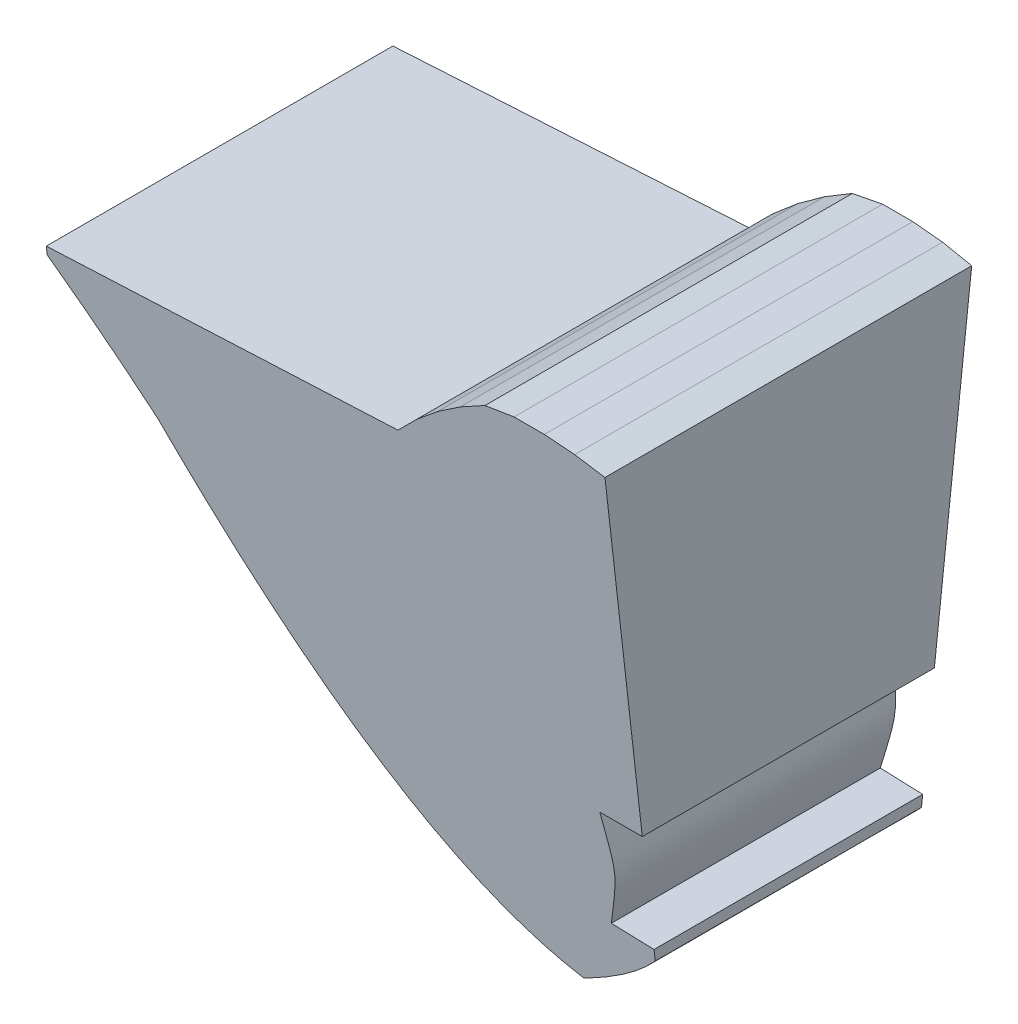
SolidWorks part; units mm, degrees
ref_plane "Alzado" through (0, 0, 0) normal (0, 0, 1) x (1, 0, 0)
ref_plane "Planta" through (0, 0, 0) normal (0, 1, 0) x (1, 0, 0)
ref_plane "Vista lateral" through (0, 0, 0) normal (1, 0, 0) x (0, 0, -1)
sketch "Croquis1" plane through (0, 0, 0) normal (0, 0, 1) x (1, 0, 0)
  line L0 (-8.9818, 12.6082) -> (-23.0359, 11.8716) construction
  line L1 (-8.9818, 12.6082) -> (-23.0359, 11.8716)
  line L2 (-8.9818, 12.6082) -> (-23.0359, 11.8716) construction
  line L4 (-8.9818, 12.6082) -> (-23.0359, 11.8716)
  line L6 (-1.3949, 1.9763) -> (0.3551, 2.2848) construction
  line L7 (-1.3949, 1.9763) -> (0.3551, 2.2848)
  line L8 (0.3551, 2.2848) -> (0.3551, 2.8423) construction
  line L9 (0.3551, 2.2848) -> (0.3551, 3.0015)
  line L10 (0.3551, -2.2848) -> (-1.3949, -2.2237) construction
  line L11 (0.3551, -2.2848) -> (-1.3949, -2.2237)
  line L12 (0.3551, 2.2848) -> (0.3551, -2.2848) construction
  line L13 (0.3551, -2.2848) -> (0.3551, -2.7233)
  line L14 (-8.9818, 12.6082) -> (-6.9949, 10.4774)
  line L15 (-23.0359, 11.5401) -> (-23.0359, 11.8716) construction
  line L16 (-23.0359, 11.5401) -> (-23.0359, 11.8716)
  arc A0 (-18.9452, 7.5409) -> (-23.0359, 11.5401) centre (-69.8841, -40.4718) ccw construction
  arc A1 (-18.9452, 7.5409) -> (-23.0359, 11.5401) centre (-69.8841, -40.4718) ccw
  spline S1 degree 2 poles (-828.7061, 3922.2202) (545.889, -3962.7836) (-262.0834, 3982.5902) knots 0.462185 0.462185 0.462185 0.537731 0.537731 0.537731 weights 1 1 1 only from (-18.9452, 7.5409) to (-2.8466, -5.0591) construction
  spline S2 degree 2 poles (-18.9452, 7.5409) (-10.215, -3.6976) (-2.8466, -5.0591) knots 0.497667 0.497667 0.497667 0.499554 0.499554 0.499554 weights 1 1 1
  spline S3 degree 2 poles (-3804.8689, 1232.5771) (3762.9122, -1369.6643) (-3716.5752, 1504.852) knots 0.462212 0.462212 0.462212 0.537836 0.537836 0.537836 weights 1 1 1 only from (0.3551, 3.0015) to (-6.9949, 10.4774) construction
  spline S4 degree 2 poles (0.3551, 3.0015) (-1.4487, 6.0584) (-6.9949, 10.4774) knots 0.500821 0.500821 0.500821 0.502013 0.502013 0.502013 weights 1 1 1
  spline S5 degree 2 poles (-1.3949, -2.2237) (-0.9075, -0.1237) (-1.3949, 1.9763) knots 0 0 0 1 1 1 weights 1 3.231801 1 construction
  spline S6 degree 2 poles (-1.3949, -2.2237) (-0.9075, -0.1237) (-1.3949, 1.9763) knots 0 0 0 1 1 1 weights 1 3.231801 1
  spline S7 degree 2 poles (-3997.263, 185.0077) (3984.2333, -348.7483) (-3965.0625, 511.2595) knots 0.462205 0.462205 0.462205 0.537778 0.537778 0.537778 weights 1 1 1 only from (-2.8466, -5.0591) to (0.3551, -2.7233) construction
  spline S8 degree 2 poles (-2.8466, -5.0591) (-0.7424, -3.9352) (0.3551, -2.7233) knots 0.498812 0.498812 0.498812 0.499413 0.499413 0.499413 weights 1 1 1
extrude "Saliente-Extruir1" add sketch "Croquis1" along normal mid plane 14.42 contours S2 S8 L13 L11 S6 L7 L9 S4 L14 L1 L16 A1
sketch "Croquis3" plane through (0, 0, 0) normal (0, 0, 1) x (1, 0, 0)
  line L0 (-6.742, 0) -> (0, 0) construction
  line L1 (-1.8181, 2) -> (-1.7771, 2.0103) construction
  line L3 (-1.8181, 2) -> (-0.1689, 2.4155) construction
  line L4 (-1.8181, 2) -> (0.3551, 3.0015)
  line L5 (0.3551, 3.0015) -> (0.3551, 0)
  line L6 (-1.9112, -2.1782) -> (0.3551, -2.2848)
  line L7 (0.3551, -2.2848) -> (0.3551, 0)
  parabola Q0 (-1.9112, -2.1782) -> (-1.8181, 2) focus (-3.3181, 0) apex (-1.3181, 0)
  dimension "D1" = 2
  dimension "D2" = 2
extrude "Cortar-Extruir1" [suppressed] cut sketch "Croquis3" against normal through all both and the other way through all
sketch "Croquis4" plane through (0, 0, 0) normal (0, 0, 1) x (1, 0, 0)
  line L0 (-1.3949, 1.9763) -> (0.3551, 2.2848) construction
  line L1 (-1.3949, 1.9763) -> (0.3551, 2.2848)
  line L2 (0.3551, 2.2848) -> (0.3551, 3.0015) construction
  line L3 (0.3551, 1.9763) -> (0.3551, 2.2848)
  line L4 (-1.3949, 1.9763) -> (0.3551, 1.9763)
  line L5 (0, 0) -> (-3.4665, 0) construction
  dimension "D1" = 0
extrude "Saliente-Extruir2" add sketch "Croquis4" along normal through all and the other way through all
sketch "Croquis7" plane through (0, 0, 0) normal (0, 0, 1) x (1, 0, 0)
  line L0 (0, 0) -> (-13.2475, 1.1183) construction
  line L1 (-14.9286, 14.3063) -> (-13.2475, 1.1183) construction
  line L2 (-13.2475, 1.1183) -> (-7.4174, -4.4688) construction
  line L3 (-13.2475, 1.1183) -> (-8.4034, 6.1732) construction
  line L4 (-14.9286, 14.3063) -> (-14.7, 12.5132) construction
  line L5 (0, 0) -> (-1.3461, -2.2254) construction
  line L6 (-69.8841, 29.5282) -> (-81.9382, 42.5765) construction
  line L7 (-69.8841, 29.5282) -> (-20.9497, 29.5282) construction
  line L8 (-17.8101, 13.1658) -> (-25.5429, 13.1658)
  line L9 (-17.6007, 6.3083) -> (-21.9246, 11.9299) construction
  line L10 (0.3551, -2.5) -> (-2.4497, -2.0473)
  line L11 (-1.3461, -2.2254) -> (-2.0075, -3.6222) construction
  line L12 (-1.3461, -2.2254) -> (-1.4547, -2.8987) construction
  line L13 (-1.3461, -2.2254) -> (-1.2286, -1.4976) construction
  line L14 (0.3551, -2.2848) -> (0.3551, -2.7233) construction
  line L15 (0.3551, -2.2848) -> (-1.3949, -2.2237) construction
  line L16 (-2.0075, -3.6222) -> (-2.6381, -4.9541) construction
  line L17 (-2.6331, -4.9434) -> (-3.7044, -5.5324) construction
  line L18 (-2.6331, -4.9434) -> (-3.2248, -3.867) construction
  line L19 (-2.6331, -4.9434) -> (-2.2174, -6.1341) construction
  line L20 (-4.0838, -4.7637) -> (-2.6213, -4.9448) construction
  line L21 (-4.0838, -4.7637) -> (-0.036, -5.9454) construction
  line L22 (-4.0838, -4.7637) -> (-3.7621, -3.6616) construction
  line L23 (-4.0838, -4.7637) -> (-5.4141, -4.1295) construction
  line L24 (-5.4141, -4.1295) -> (-8.69, -2.5677) construction
  line L25 (-8.69, -2.5677) -> (-6.8421, -3.7725) construction
  line L26 (-8.69, -2.5677) -> (-7.9481, -1.4297) construction
  line L27 (-11.4407, -0.2002) -> (-8.69, -2.5677) construction
  line L28 (-11.4407, -0.2002) -> (-14.8546, 2.738) construction
  line L29 (-14.8546, 2.738) -> (-14.5337, 2.3989) construction
  line L30 (-14.8546, 2.738) -> (-14.6199, 2.9602) construction
  line L31 (-17.6007, 6.3083) -> (-14.8546, 2.738) construction
  line L32 (-8.9818, 12.6082) -> (-23.0359, 11.8716) construction
  line L33 (-8.9818, 12.6082) -> (-23.0359, 11.8716)
  line L34 (-21.9246, 11.9299) -> (-21.9826, 13.0367) construction
  line L35 (-21.9246, 11.9299) -> (-23.4156, 13.0367) construction
  arc A0 (-18.9452, 7.5409) -> (-23.0359, 11.5401) centre (-69.8841, -40.4718) ccw construction
  spline S0 degree 2 poles (-828.7061, 3922.2202) (545.889, -3962.7836) (-262.0834, 3982.5902) knots 0.462185 0.462185 0.462185 0.537731 0.537731 0.537731 weights 1 1 1 only from (-18.9452, 7.5409) to (-2.8466, -5.0591) construction
  spline S1 degree 2 poles (-18.6263, 7.1332) (-10.0803, -3.7225) (-2.8466, -5.0591) knots 0.497702 0.497702 0.497702 0.499554 0.499554 0.499554 weights 1 1 1 construction
  spline S3 degree 2 poles (-3997.263, 185.0077) (3984.2333, -348.7483) (-3965.0625, 511.2595) knots 0.462205 0.462205 0.462205 0.537778 0.537778 0.537778 weights 1 1 1 only from (-2.8466, -5.0591) to (0.3551, -2.7233) construction
  spline S4 degree 2 poles (-2.8466, -5.0591) (-2.7385, -5.0013) (-2.6331, -4.9434) knots 0.498812 0.498812 0.498812 0.498843 0.498843 0.498843 weights 1 1 1
  dimension "D1" = 2.5
  dimension "D2" = 22
  dimension "D3" = 16.17
  dimension "D4" = 54.138
  dimension "D5" = 34.566
  dimension "D6" = 50.413
sketch "Croquis6" plane through (0, 0, 0) normal (1, 0, 0) x (0, 0, -1)
  line L0 (7.21, 12.6082) -> (7.21, 10.4774) construction
  line L1 (7.21, 12.6082) -> (7.21, -5.0591)
  line L2 (-7.21, 12.6082) -> (-7.21, 10.4774) construction
  line L3 (-7.21, 12.6082) -> (-7.21, -5.0591)
  line L4 (-7.21, -5.0591) -> (7.21, -5.0591) construction
  line L5 (-7.21, -5.0591) -> (-5.21, -5.0591)
  line L6 (7.21, 12.6082) -> (5.21, -5.0591)
  line L7 (-7.21, 12.6082) -> (-5.21, -5.0591)
  line L8 (5.21, -5.0591) -> (7.21, -5.0591)
  dimension "D1" = 2
  dimension "D2" = 2
extrude "Cortar-Extruir2" cut sketch "Croquis6" against normal through all and the other way through all
sketch "Croquis8" plane through (0, 0, 0) normal (0, 0, 1) x (1, 0, 0)
  line L0 (-8.9818, 12.6082) -> (-23.0359, 11.8716) construction
  line L1 (-9.7264, 12.5691) -> (0.3551, 15.5338) construction
  line L2 (0.3551, 1.9763) -> (0.3551, 3.0015) construction
  line L3 (0.3551, 3.0015) -> (0.3551, 15.5338)
  line L5 (-8.487, 12.6341) -> (-7.6094, 13.5117)
  line L6 (-7.6094, 13.5117) -> (-6.6586, 14.3095)
  line L7 (-6.6586, 14.3095) -> (-5.6419, 15.0214)
  line L8 (-5.6419, 15.0214) -> (-4.567, 15.642)
  line L9 (-4.567, 15.642) -> (-3.3447, 15.8575)
  line L10 (-3.3447, 15.8575) -> (-2.1036, 15.8575)
  line L11 (-2.1036, 15.8575) -> (-0.8672, 15.7493)
  line L12 (-0.8672, 15.7493) -> (0.3551, 15.5338)
  line L13 (-0.5199, 1.9763) -> (-9.282, 12.9915) construction
  line L14 (-9.282, 12.9915) -> (-9.6919, 13.4229) construction
  line L15 (-9.282, 12.9915) -> (-9.8512, 13.838) construction
  line L16 (-0.5199, 1.9763) -> (-8.0482, 13.0729) construction
  line L17 (-8.0482, 13.0729) -> (-8.9345, 13.9592) construction
  line L18 (-0.5199, 1.9763) -> (-7.134, 13.9106) construction
  line L19 (0.3551, 1.9763) -> (-1.3949, 1.9763) construction
  line L20 (-7.134, 13.9106) -> (-7.3142, 14.1254) construction
  line L21 (-0.5199, 1.9763) -> (-6.1502, 14.6655) construction
  line L22 (-0.5199, 1.9763) -> (-5.1045, 15.3317) construction
  line L23 (-5.1045, 15.3317) -> (-5.8458, 16.6158) construction
  line L24 (-0.5199, 1.9763) -> (-3.9559, 15.7497) construction
  line L25 (-3.9559, 15.7497) -> (-4.1959, 17.1108) construction
  line L26 (-0.5199, 1.9763) -> (-2.7242, 15.8575) construction
  line L27 (-2.7242, 15.8575) -> (-2.7242, 17.3568) construction
  line L28 (-0.5199, 1.9763) -> (-1.4854, 15.8034) construction
  line L29 (-1.4854, 15.8034) -> (-1.3613, 17.2215) construction
  line L30 (-0.5199, 1.9763) -> (-0.256, 15.6416) construction
  line L31 (-0.256, 15.6416) -> (-0.1544, 16.2178) construction
  line L32 (-7.134, 13.9106) -> (-7.8177, 14.7255) construction
  line L33 (-6.1502, 14.6655) -> (-6.7711, 15.5522) construction
  line L34 (-9.7264, 12.5691) -> (-9.7264, 19.4167) construction
  line L35 (-0.256, 15.6416) -> (0.0328, 17.2794) construction
  line L36 (-9.7264, 12.5691) -> (-8.487, 12.6341)
  spline S0 degree 2 poles (-1851.9698, 781.7085) (1883.9916, -685.7524) (-1911.5868, 588.043) knots 0.476049 0.476049 0.476049 0.529551 0.529551 0.529551 weights 1 1 1 only from (-6.9949, 10.4774) to (0.3551, 3.0015) construction
  spline S1 degree 2 poles (-9.7264, 12.5691) (-1.8611, 6.7573) (0.3551, 3.0015) knots 0.500548 0.500548 0.500548 0.502013 0.502013 0.502013 weights 1 1 1
  dimension "D1" = 5.039
  dimension "D2" = 95
  dimension "D3" = 80
  dimension "D4" = 60
  dimension "D5" = 45
  dimension "D6" = 50
  dimension "D7" = 55
  dimension "D8" = 90
  dimension "D9" = 100
extrude "Saliente-Extruir3" add sketch "Croquis8" along normal up to surface and the other way up to surface up to face at (-6.8548, 3.8413, 6.2176) other way up to face at (-6.9269, 3.652, -6.1961)
